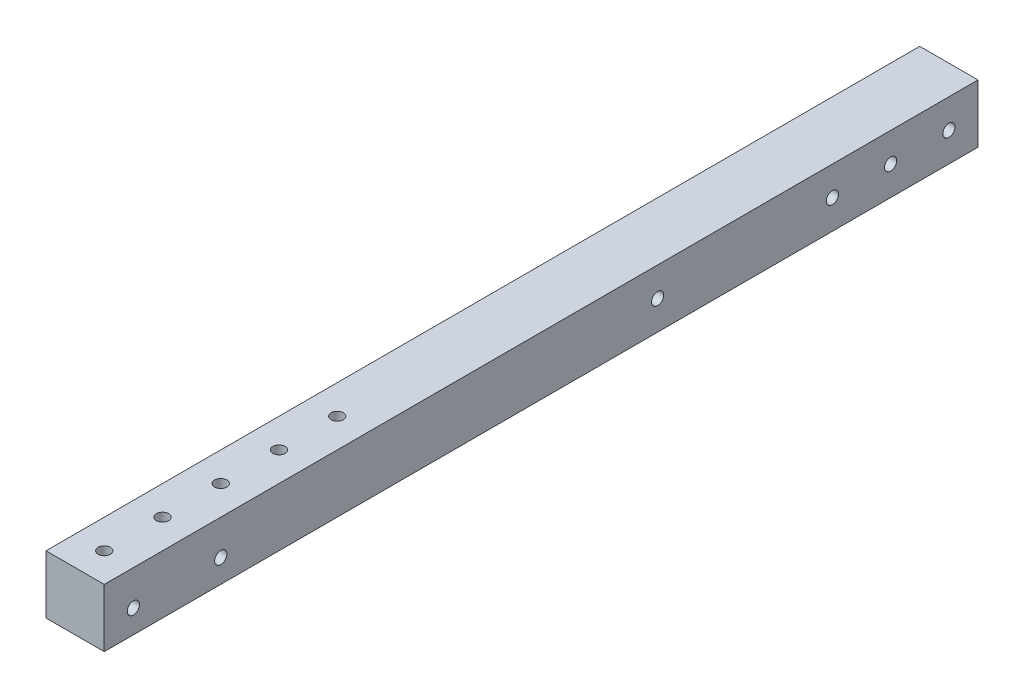
SolidWorks part; units mm, degrees
ref_plane "前视基准面" through (0, 0, 0) normal (0, 0, 1) x (1, 0, 0)
ref_plane "上视基准面" through (0, 0, 0) normal (0, 1, 0) x (1, 0, 0)
ref_plane "右视基准面" through (0, 0, 0) normal (1, 0, 0) x (0, 0, -1)
sketch "草图1" plane through (0, 0, 0) normal (0, 0, 1) x (1, 0, 0)
  line L1 (-10, 10) -> (10, 10)
  line L2 (-10, 10) -> (-10, -10)
  line L3 (-10, -10) -> (10, -10)
  line L4 (10, 10) -> (10, -10)
  line L5 (-10, 10) -> (10, -10) construction
  line L6 (-10, -10) -> (10, 10) construction
  point P0 (0, 0)
  dimension "D1" = 20
  dimension "D2" = 20
extrude "凸台-拉伸1" add sketch "草图1" along normal blind 300
sketch "草图2" plane through (10, 0, 0) normal (1, 0, 0) x (0, 0, -1)
  line L0 (-150, 10) -> (-150, -10) construction
  line L1 (-300, 10) -> (0, 10) construction
  line L2 (-300, -10) -> (0, -10) construction
sketch "草图3" plane through (10, 0, 0) normal (1, 0, 0) x (0, 0, -1)
  line L0 (0, -10) -> (0, 10) construction
  line L1 (-300, 10) -> (0, 10) construction
  line L2 (-150, 10) -> (-150, -10)
  circle A0 centre (-10, 0) radius 2.1
  circle A1 centre (-30, 0) radius 2.1
  dimension "D1" = 10
  dimension "D3" = 4.2
  dimension "D2" = 10
  dimension "D5" = 20
  dimension "D4" = 2
extrude "切除-拉伸1" cut sketch "草图3" against normal through all
sketch "草图4" plane through (10, 0, 0) normal (1, 0, 0) x (0, 0, -1)
  line L1 (-300, 10) -> (0, 10) construction
  line L2 (0, -10) -> (0, 10) construction
  circle A1 centre (-110, 0) radius 2.1
  dimension "D1" = 110
  dimension "D3" = 4.2
  dimension "D2" = 10
extrude "切除-拉伸2" cut sketch "草图4" against normal through all
sketch "草图5" plane through (10, 0, 0) normal (1, 0, 0) x (0, 0, -1)
  line L0 (-300, 10) -> (0, 10) construction
  circle A1 centre (-50, 0) radius 2.1
  circle A3 centre (-30, 0) radius 2.1 construction
  dimension "D1" = 4.2
  dimension "D4" = 20
  dimension "D5" = 10
extrude "切除-拉伸3" cut sketch "草图5" against normal through all
sketch "草图7" plane through (0, -10, 0) normal (0, -1, 0) x (1, 0, 0)
  line L0 (-10, 300) -> (10, 300) construction
  line L1 (-10, 300) -> (-10, 0) construction
  circle A0 centre (0, 290) radius 2.1
  circle A1 centre (0, 270) radius 2.1
  circle A2 centre (0, 250) radius 2.1
  circle A3 centre (0, 230) radius 2.1
  circle A4 centre (0, 210) radius 2.1
  dimension "D1" = 10
  dimension "D3" = 4.2
  dimension "D2" = 10
  dimension "D5" = 20
  dimension "D4" = 5
extrude "切除-拉伸4" cut sketch "草图7" against normal through all
sketch "草图8" plane through (10, 0, 0) normal (1, 0, 0) x (0, 0, -1)
  line L0 (-300, -10) -> (-300, 10) construction
  line L1 (-300, 10) -> (0, 10) construction
  circle A0 centre (-290, -2) radius 2.1
  circle A1 centre (-260, -2) radius 2.1
  dimension "D1" = 10
  dimension "D3" = 4.2
  dimension "D5" = 30
  dimension "D2" = 12
  dimension "D4" = 2
extrude "切除-拉伸5" cut sketch "草图8" against normal through all
